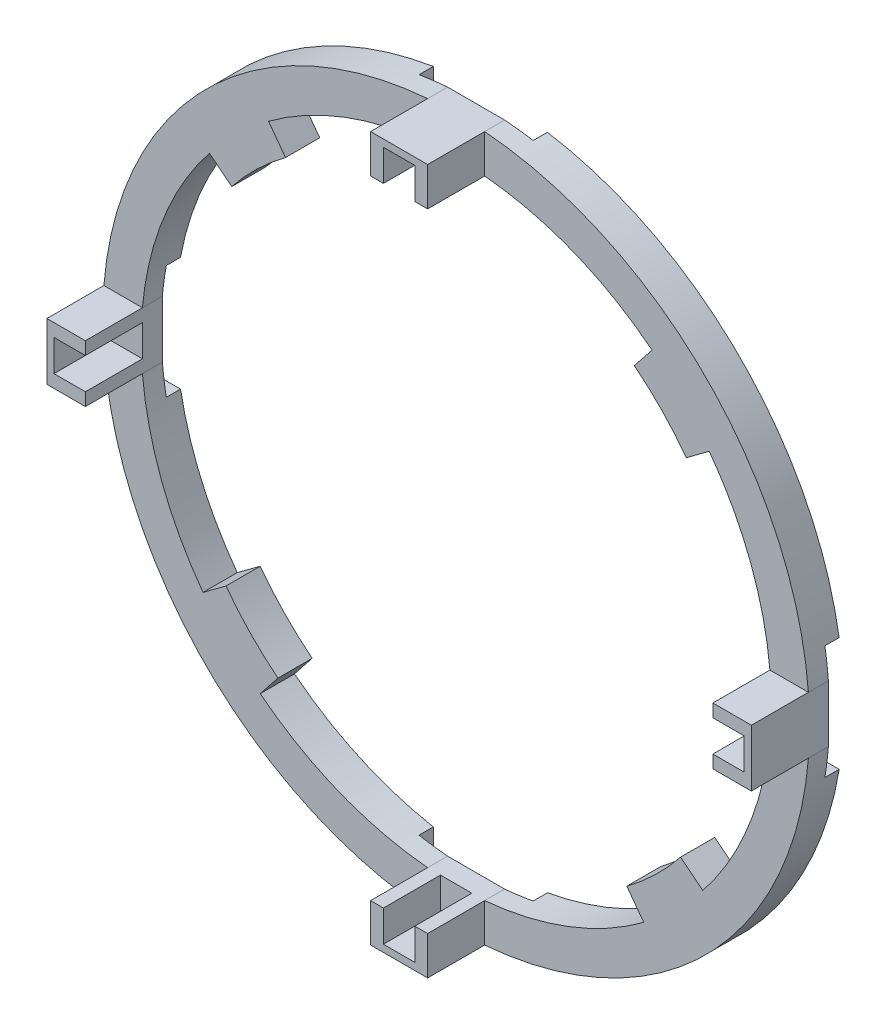
SolidWorks part; units mm, degrees
ref_plane "Front Plane" through (0, 0, 0) normal (0, 0, 1) x (1, 0, 0)
ref_plane "Top Plane" through (0, 0, 0) normal (0, 1, 0) x (1, 0, 0)
ref_plane "Right Plane" through (0, 0, 0) normal (1, 0, 0) x (0, 0, -1)
sketch "Sketch2" plane through (0, 0, 0) normal (0, 0, 1) x (1, 0, 0)
  line L0 (0, 150.4702) -> (0, -145.6395) construction
  line L1 (-120, 0) -> (120, 0) construction
  line L35 (110, 10) -> (123.5, 10)
  line L37 (110, -10) -> (123.5, -10)
  line L38 (123.5, 10) -> (123.5, -10)
  line L39 (110, 10) -> (121, -1) construction
  line L40 (110, -10) -> (121, 1) construction
  line L41 (114.5, 5.5) -> (121, 5.5)
  line L43 (114.5, -5.5) -> (121, -5.5)
  line L45 (114.5, 5.5) -> (121, -1) construction
  line L46 (114.5, -5.5) -> (121, 1) construction
  line L47 (10, -110) -> (10, -123.5)
  line L48 (10, -123.5) -> (-10, -123.5)
  line L49 (-10, -110) -> (-10, -123.5)
  line L51 (5.5, -114.5) -> (5.5, -121)
  line L53 (-5.5, -114.5) -> (-5.5, -121)
  line L55 (-110, -10) -> (-123.5, -10)
  line L56 (-123.5, -10) -> (-123.5, 10)
  line L57 (-110, 10) -> (-123.5, 10)
  line L59 (-114.5, -5.5) -> (-121, -5.5)
  line L61 (-114.5, 5.5) -> (-121, 5.5)
  line L62 (-10, 110) -> (-5.5, 110)
  line L63 (-10, 110) -> (-10, 123.5)
  line L64 (-10, 123.5) -> (10, 123.5)
  line L65 (10, 110) -> (10, 123.5)
  line L67 (-5.5, 114.5) -> (-5.5, 121)
  line L69 (5.5, 114.5) -> (5.5, 121)
  line L70 (-5.5, 114.5) -> (-5.5, 110)
  line L71 (-121, -5.5) -> (-121, 5.5)
  line L72 (5.5, 114.5) -> (5.5, 110)
  line L73 (5.5, 110) -> (10, 110)
  line L74 (110, -10) -> (110, -5.5)
  line L75 (110, -5.5) -> (114.5, -5.5)
  line L76 (110, 10) -> (110, 5.5)
  line L77 (110, 5.5) -> (114.5, 5.5)
  line L78 (-10, -110) -> (-5.5, -110)
  line L79 (-5.5, -110) -> (-5.5, -114.5)
  line L80 (10, -110) -> (5.5, -110)
  line L81 (5.5, -110) -> (5.5, -114.5)
  line L82 (-114.5, -5.5) -> (-110, -5.5)
  line L83 (-114.5, 5.5) -> (-110, 5.5)
  line L84 (-110, -5.5) -> (-110, -10)
  line L85 (-110, 5.5) -> (-110, 10)
  line L86 (5.5, -121) -> (-5.5, -121)
  line L89 (-5.5, 121) -> (5.5, 121)
  line L91 (121, 5.5) -> (121, -5.5)
  circle A0 centre (0, 0) radius 120 construction
  point P29 (0, -145.6395)
  point P37 (0, 0)
  point P43 (0, 0)
  dimension "D5" = 121
  dimension "D8" = 121
  dimension "D1" = 240
  dimension "D2" = 20
  dimension "D3" = 123.5
  dimension "D4" = 121
  dimension "D6" = 4
  dimension "D7" = 121
  dimension "D9" = 110
extrude "Boss-Extrude1" add sketch "Sketch2" along normal blind 20
sketch "Sketch3" plane through (0, 0, 0) normal (0, 0, -1) x (-1, 0, 0)
  line L3 (0, 128.3867) -> (0, -130.2656) construction
  line L4 (-130.8918, 0) -> (131.5181, 0) construction
  line L6 (-88.7317, 65.7775) -> (-80.6983, 59.8223)
  line L8 (-62.4655, 78.6702) -> (-68.6838, 86.5016)
  line L10 (0, 0) -> (-108.0248, 104.5) construction
  line L11 (65.7775, 88.7317) -> (59.8223, 80.6983)
  line L12 (78.6702, 62.4655) -> (86.5016, 68.6838)
  line L34 (-10, 123.5) -> (10, 123.5)
  line L47 (123.5, 10) -> (123.5, -10)
  line L53 (10, -123.5) -> (-10, -123.5)
  line L54 (88.7317, -65.7775) -> (80.6983, -59.8223)
  line L59 (-123.5, -10) -> (-123.5, 10)
  line L60 (-110, -10) -> (-110, -5.5)
  line L66 (62.4655, -78.6702) -> (68.6838, -86.5016)
  line L67 (-65.7775, -88.7317) -> (-59.8223, -80.6983)
  line L68 (-78.6702, -62.4655) -> (-86.5016, -68.6838)
  line L72 (-110, 5.5) -> (-110, 10)
  line L73 (-110, 5.5) -> (-110, -5.5)
  line L74 (-10, -110) -> (10, -110)
  line L82 (110, -10) -> (110, 10)
  line L86 (-10, 110) -> (10, 110)
  arc A12 (-10, 123.5) -> (-123.5, 10) centre (0, 0) ccw
  arc A13 (-10, 110) -> (-68.6838, 86.5016) centre (0, 0) ccw
  arc A14 (-110, -10) -> (-86.5016, -68.6838) centre (0, 0) ccw
  arc A15 (-123.5, -10) -> (-10, -123.5) centre (0, 0) ccw
  arc A16 (10, -123.5) -> (123.5, -10) centre (0, 0) ccw
  arc A17 (10, -110) -> (68.6838, -86.5016) centre (0, 0) ccw
  arc A18 (123.5, 10) -> (10, 123.5) centre (0, 0) ccw
  arc A19 (110, 10) -> (86.5016, 68.6838) centre (0, 0) ccw
  arc A20 (-80.6983, 59.8223) -> (-62.4655, 78.6702) centre (0, 0) cw
  arc A21 (59.8223, 80.6983) -> (78.6702, 62.4655) centre (0, 0) cw
  arc A22 (80.6983, -59.8223) -> (62.4655, -78.6702) centre (0, 0) cw
  arc A23 (-59.8223, -80.6983) -> (-78.6702, -62.4655) centre (0, 0) cw
  arc A24 (-88.7317, 65.7775) -> (-110, 10) centre (0, 0) ccw
  arc A25 (65.7775, 88.7317) -> (10, 110) centre (0, 0) ccw
  arc A26 (88.7317, -65.7775) -> (110, -10) centre (0, 0) ccw
  arc A27 (-65.7775, -88.7317) -> (-10, -110) centre (0, 0) ccw
  point P34 (-72.1996, 69.8437)
  point P42 (0, 0)
  point P59 (0, 0)
  dimension "D1" = 4
  dimension "D2" = 15
  dimension "D3" = 10
  dimension "D4" = 110.4536
  dimension "D5" = 4
  dimension "D6" = 110
extrude "Boss-Extrude2" add sketch "Sketch3" along normal blind 12
sketch "Sketch5" plane through (0, 0, -12) normal (0, 0, -1) x (-1, 0, 0)
  line L0 (-177.5716, 0) -> (184.0171, 0) construction
  line L1 (0, 131.8091) -> (0, -144.6999) construction
  line L2 (-123.5, -10) -> (-123.5, 10) construction
  line L3 (-104.25, -20) -> (-129.25, -20)
  line L4 (-104.25, -20) -> (-104.25, 20)
  line L5 (-104.25, 20) -> (-129.25, 20)
  line L6 (-129.25, -20) -> (-129.25, 20)
  line L7 (-104.25, -20) -> (-129.25, 20) construction
  line L8 (-104.25, 20) -> (-129.25, -20) construction
  line L9 (-110, -10) -> (-110, 10) construction
  line L10 (-20, 104.25) -> (20, 104.25)
  line L11 (-20, 104.25) -> (-20, 129.25)
  line L12 (-20, 129.25) -> (20, 129.25)
  line L13 (20, 104.25) -> (20, 129.25)
  line L14 (104.25, 20) -> (104.25, -20)
  line L15 (104.25, 20) -> (129.25, 20)
  line L16 (129.25, 20) -> (129.25, -20)
  line L17 (104.25, -20) -> (129.25, -20)
  line L18 (20, -104.25) -> (-20, -104.25)
  line L19 (20, -104.25) -> (20, -129.25)
  line L20 (20, -129.25) -> (-20, -129.25)
  line L21 (-20, -104.25) -> (-20, -129.25)
  point P5 (-116.75, 0)
  point P29 (0, 0)
  dimension "D1" = 13.5
  dimension "D2" = 6.75
  dimension "D3" = 25
  dimension "D4" = 40
extrude "Cut-Extrude1" cut sketch "Sketch5" against normal blind 5
